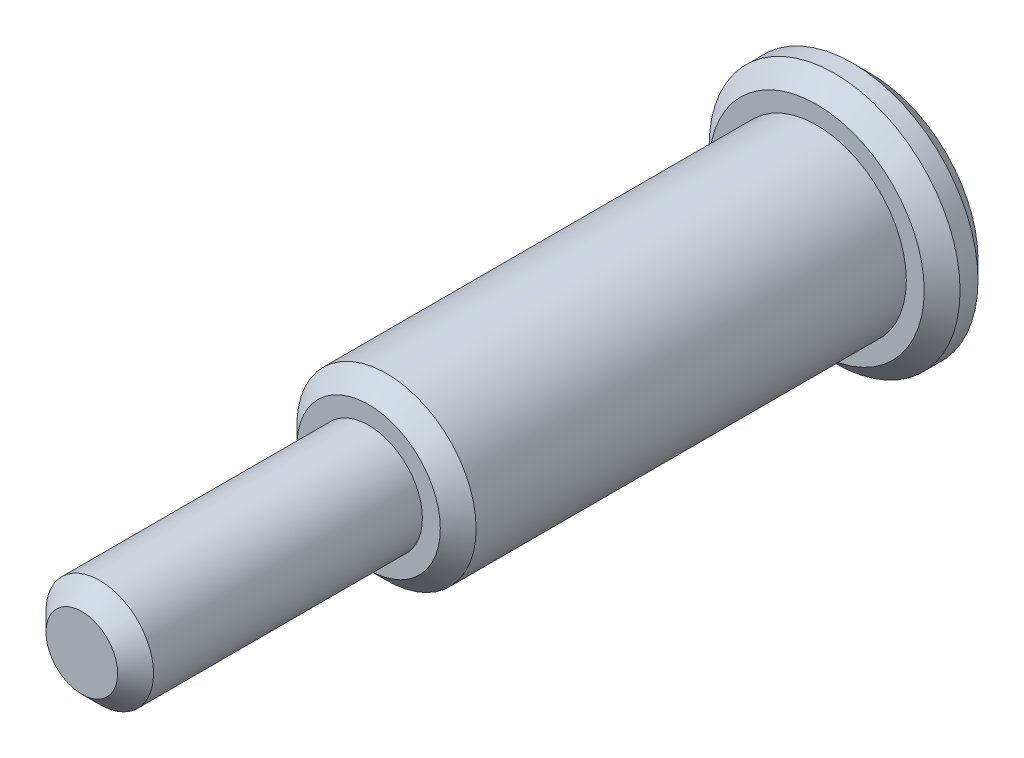
SolidWorks part; units mm, degrees
ref_plane "Front Plane" through (0, 0, 0) normal (0, 0, 1) x (1, 0, 0)
ref_plane "Top Plane" through (0, 0, 0) normal (0, 1, 0) x (1, 0, 0)
ref_plane "Right Plane" through (0, 0, 0) normal (1, 0, 0) x (0, 0, -1)
sketch "Sketch1" plane through (0, 0, 0) normal (0, 1, 0) x (1, 0, 0)
  line L0 (0, 0) -> (7, 0)
  line L1 (7, 0) -> (7, -3)
  line L2 (7, -3) -> (5, -3)
  line L3 (5, -3) -> (5, -28)
  line L4 (5, -28) -> (3, -28)
  line L5 (3, -28) -> (3, -44)
  line L6 (3, -44) -> (0, -44)
  line L7 (0, -44) -> (0, 0)
  dimension "D1" = 5
  dimension "D2" = 3
  dimension "D3" = 7
  dimension "D4" = 3
  dimension "D5" = 25
  dimension "D6" = 16
revolve "Revolve1" add sketch "Sketch1" angle 360 about L7
chamfer "Chamfer1" distance 1 angle 45 4 edges at (3, 0, 44) (5, 0, 28) (7, 0, 0) (7, 0, 3)
